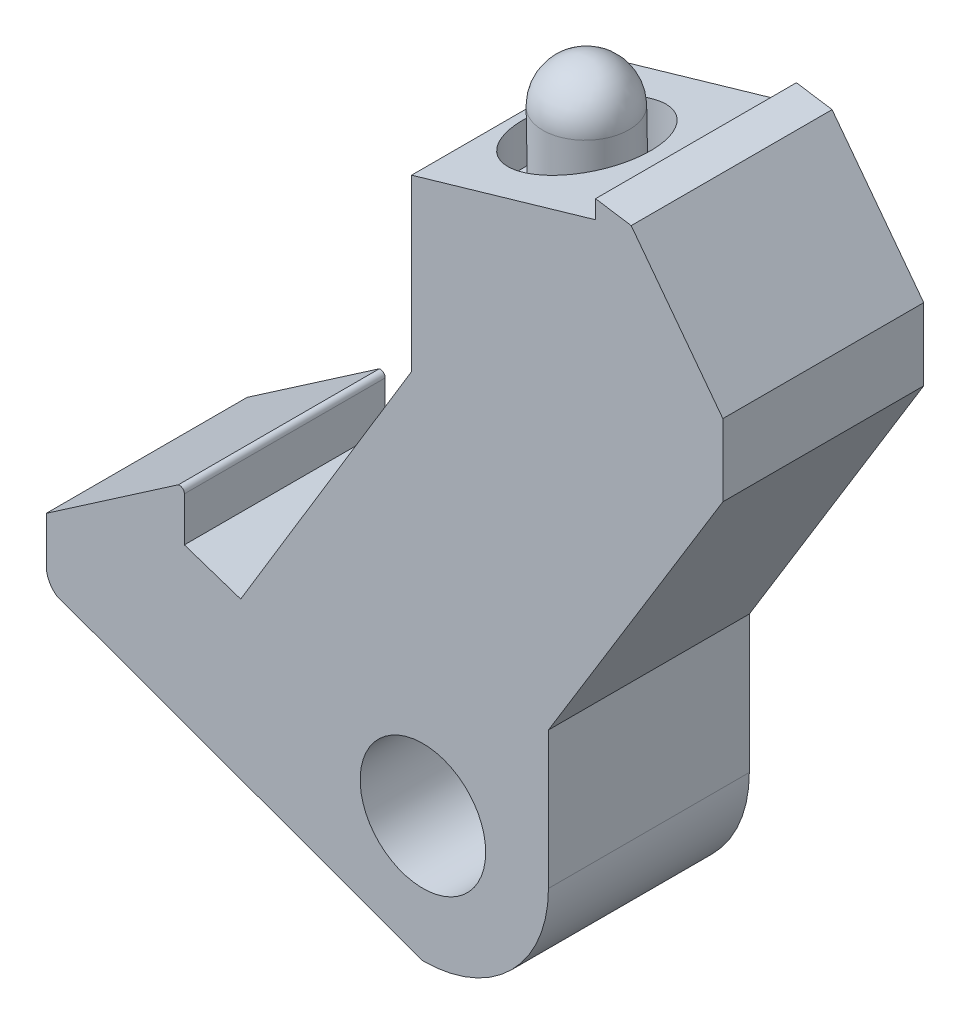
SolidWorks part; units mm, degrees
ref_plane "정면" through (0, 0, 0) normal (0, 0, 1) x (1, 0, 0)
ref_plane "윗면" through (0, 0, 0) normal (0, 1, 0) x (1, 0, 0)
ref_plane "우측면" through (0, 0, 0) normal (1, 0, 0) x (0, 0, -1)
sketch "스케치1" plane through (0, 0, 0) normal (0, 0, 1) x (1, 0, 0)
  line L0 (6.8756, 24) -> (-0.4511, 21.8755)
  line L1 (-15, 1.1119) -> (-15, 2.938)
  line L2 (8.2956, 24.5088) -> (11.9458, 19.6763)
  line L3 (-9.5, 6.359) -> (-9.5, 4.5986)
  line L6 (10.1123, 13.8134) -> (11.9458, 16.8074)
  line L7 (10.1123, 13.8134) -> (5, 5.4649)
  line L8 (-14.5829, 0.2994) -> (0, -5)
  line L9 (5, 0) -> (5, 3.8348)
  line L10 (-6.5, 3.5986) -> (-0.8913, 3.5986) construction
  line L11 (-7.2581, 3.8513) -> (-9.5, 4.5986)
  line L14 (-9.7358, 6.5557) -> (-15, 2.938)
  line L15 (5, 5.4649) -> (5, 3.8348)
  line L16 (6.8756, 24.7282) -> (6.8756, 24)
  line L17 (6.8756, 24.7282) -> (8.2956, 24.5088)
  line L18 (11.9458, 16.8074) -> (11.9458, 19.6763)
  line L21 (-7.2581, 3.8513) -> (-0.4511, 15.1015)
  line L22 (-0.4511, 15.1015) -> (-0.4511, 21.8755)
  circle A0 centre (0, 0) radius 2.5
  arc A1 (0, -5) -> (5, 0) centre (0, 0) ccw
  arc A3 (-9.7358, 6.5557) -> (-9.5, 6.359) centre (-9.7, 6.359) cw
  arc A5 (-14.5829, 0.2994) -> (-15, 1.1119) centre (-14, 1.1119) cw
  point P18 (-9.5, 6.5986)
  point P20 (-7.1958, -5)
  point P24 (-15, 0.5986)
  point P27 (-15, 6.5986)
  dimension "D1" = 5
  dimension "D2" = 10
  dimension "D6" = 0.2
  dimension "D3" = 6
  dimension "D4" = 9.6047
  dimension "D7" = 5.5
extrude "보스-돌출1" add sketch "스케치1" along normal blind 8
sketch "스케치3" plane through (-5.8861, 20.2996, 0) normal (-0.2785, 0.9604, 0) x (0.9604, 0.2785, 0)
  circle A0 centre (8.8231, -4) radius 2.5
  dimension "D1" = 5
sketch "스케치5" plane through (-1.605, -4.4167, 0) normal (-0.3415, -0.9399, 0) x (0.9399, -0.3415, 0)
  line L0 (-13.8082, 8) -> (1.7077, 0) construction
  line L1 (-6.0503, 4) -> (-13.8082, 4) construction
  line L2 (-13.8082, 8) -> (-13.8082, 0) construction
  circle A0 centre (-9.9292, 4) radius 3
  dimension "D1" = 6
extrude "컷-돌출2" cut sketch "스케치5" against normal blind 3
sketch "스케치7" plane through (-0.5804, -1.5971, 0) normal (-0.3415, -0.9399, 0) x (0.9399, -0.3415, 0)
  circle A0 centre (-9.9292, 4) radius 2
extrude "보스-돌출3" add sketch "스케치7" along normal blind 3
fillet "필렛5" radius 2 1 edges at (-9.0574, -1.7085, 4)
sketch "스케치8" plane through (0, 0, 8) normal (0, 0, 1) x (1, 0, 0)
  line L0 (-0.4511, 21.8755) -> (10.1207, 22.0926)
  line L1 (11.9458, 19.6763) -> (8.2956, 24.5088) construction
ref_plane "평면1" through (-0.4491, 21.8756, 0) normal (0.0205, -0.9998, 0) x (-0.9998, -0.0205, 0)
sketch "스케치9" plane through (-0.4491, 21.8756, 0) normal (0.0205, -0.9998, 0) x (-0.9998, -0.0205, 0)
  line L0 (0.0021, -8) -> (0.0021, 0) construction
  circle A0 centre (-2.9979, -4) radius 2.55
  point P2 (0.0021, -4)
  dimension "D2" = 5.1
  dimension "D1" = 3
extrude "컷-돌출3" cut sketch "스케치9" against normal mid plane 3
sketch "스케치10" plane through (-0.4183, 20.3759, 0) normal (-0.0205, 0.9998, 0) x (0.9998, 0.0205, 0)
  circle A0 centre (2.9979, -4) radius 1.7
  dimension "D1" = 3.4
extrude "보스-돌출4" add sketch "스케치10" along normal blind 5
fillet "필렛6" radius 1.7 1 edges at (0.7767, 25.4015, 4)
